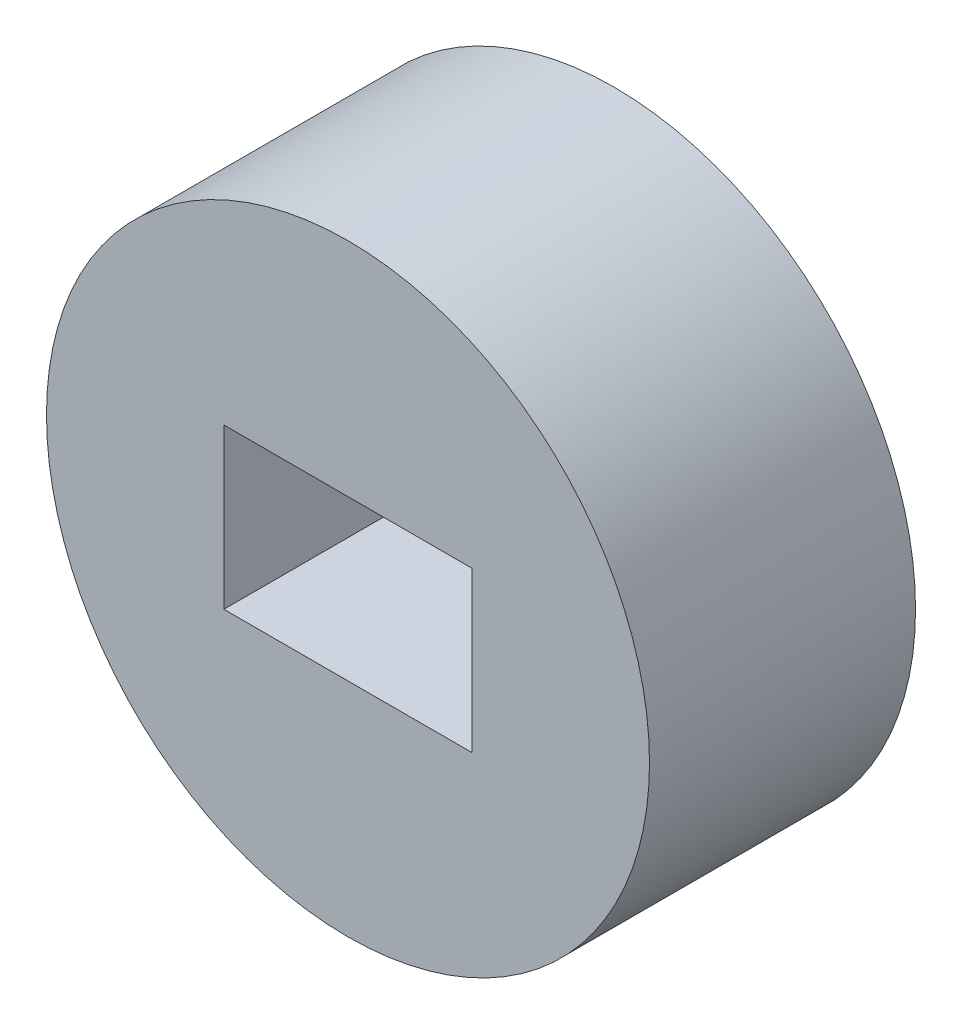
SolidWorks part; units mm, degrees
ref_plane "Alzado" through (0, 0, 0) normal (0, 0, 1) x (1, 0, 0)
ref_plane "Planta" through (0, 0, 0) normal (0, 1, 0) x (1, 0, 0)
ref_plane "Vista lateral" through (0, 0, 0) normal (1, 0, 0) x (0, 0, -1)
sketch "Model" plane through (0, 0, 0) normal (0, 0, 1) x (1, 0, 0)
  line L0 (11.4697, 294.4515) -> (11.4697, 292.6515)
  line L1 (14.2697, 294.4515) -> (11.4697, 294.4515)
  line L2 (14.2697, 292.6515) -> (14.2697, 294.4515)
  line L3 (11.4697, 292.6515) -> (14.2697, 292.6515)
  circle A0 centre (12.8697, 293.5515) radius 3.4
extrude "Saliente-Extruir1" add sketch "Model" along normal blind 3
